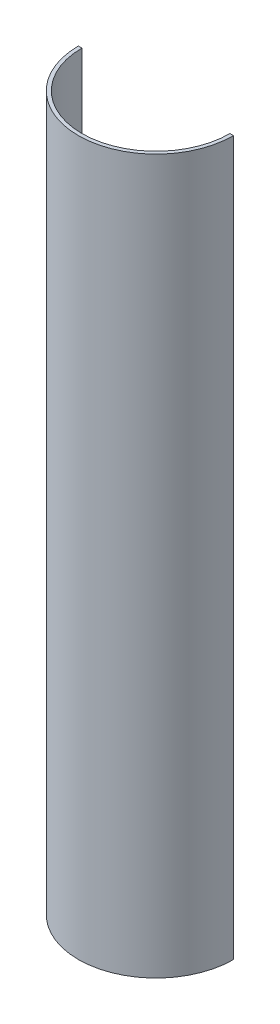
SolidWorks part; units mm, degrees
material "AISI 304"
ref_plane "Front Plane" through (0, 0, 0) normal (0, 0, 1) x (1, 0, 0)
ref_plane "Top Plane" through (0, 0, 0) normal (0, 1, 0) x (1, 0, 0)
ref_plane "Right Plane" through (0, 0, 0) normal (1, 0, 0) x (0, 0, -1)
sketch "Sketch1" plane through (0, 0, 0) normal (0, 1, 0) x (1, 0, 0)
  line L0 (84, 0) -> (86, 0)
  line L1 (-1, 0) -> (1, 0)
  arc A0 (84, 0) -> (1, 0) centre (42.5, 0) cw
  arc A1 (86, 0) -> (-1, 0) centre (42.5, 0) cw
  dimension "D4" = 2
extrude "Boss-Extrude1" add sketch "Sketch1" along normal blind 400
